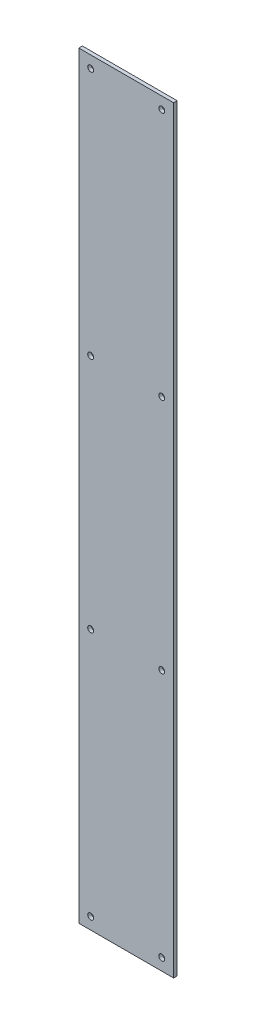
SolidWorks part; units mm, degrees
material "Acrylic (Medium-high impact)"
ref_plane "Front Plane" through (0, 0, 0) normal (0, 0, 1) x (1, 0, 0)
ref_plane "Top Plane" through (0, 0, 0) normal (0, 1, 0) x (1, 0, 0)
ref_plane "Right Plane" through (0, 0, 0) normal (1, 0, 0) x (0, 0, -1)
sketch "Sketch2" plane through (0, 0, 0) normal (0, 0, 1) x (1, 0, 0)
  line L1 (-27.1074, 80.9917) -> (52.8926, 80.9917)
  line L2 (-27.1074, 80.9917) -> (-27.1074, -559.0083)
  line L3 (-27.1074, -559.0083) -> (52.8926, -559.0083)
  line L4 (52.8926, 80.9917) -> (52.8926, -559.0083)
  dimension "D1" = 80
  dimension "D2" = 640
extrude "Boss-Extrude1" add sketch "Sketch2" along normal blind 3
sketch "Sketch3" plane through (0, 0, 3) normal (0, 0, 1) x (1, 0, 0)
  line L0 (-27.1074, -559.0083) -> (52.8926, -559.0083) construction
  line L1 (52.8926, -559.0083) -> (52.8926, 80.9917) construction
  line L2 (52.8926, 80.9917) -> (-27.1074, 80.9917) construction
  circle A0 centre (42.8926, -549.0083) radius 2.5
  circle A1 centre (-17.1074, -549.0083) radius 2.5
  circle A2 centre (-17.1074, -339.0083) radius 2.5
  circle A3 centre (-17.1074, 70.9917) radius 2.5
  circle A4 centre (-17.1074, -139.0083) radius 2.5
  circle A6 centre (42.8926, 70.9917) radius 2.5
  circle A7 centre (42.8926, -139.0083) radius 2.5
  circle A9 centre (42.8926, -339.0083) radius 2.5
  point P16 (-16.5715, 79.8062)
  point P27 (0, 0)
  dimension "D1" = 5
  dimension "D3" = 10
  dimension "D5" = 10
  dimension "D6" = 10
  dimension "D9" = 10
  dimension "D14" = 10
  dimension "D4" = 210
  dimension "D8" = 10
  dimension "D10" = 200
  dimension "D2" = 10
  dimension "D7" = 210
  dimension "D11" = 210
extrude "Cut-Extrude1" cut sketch "Sketch3" against normal through all
